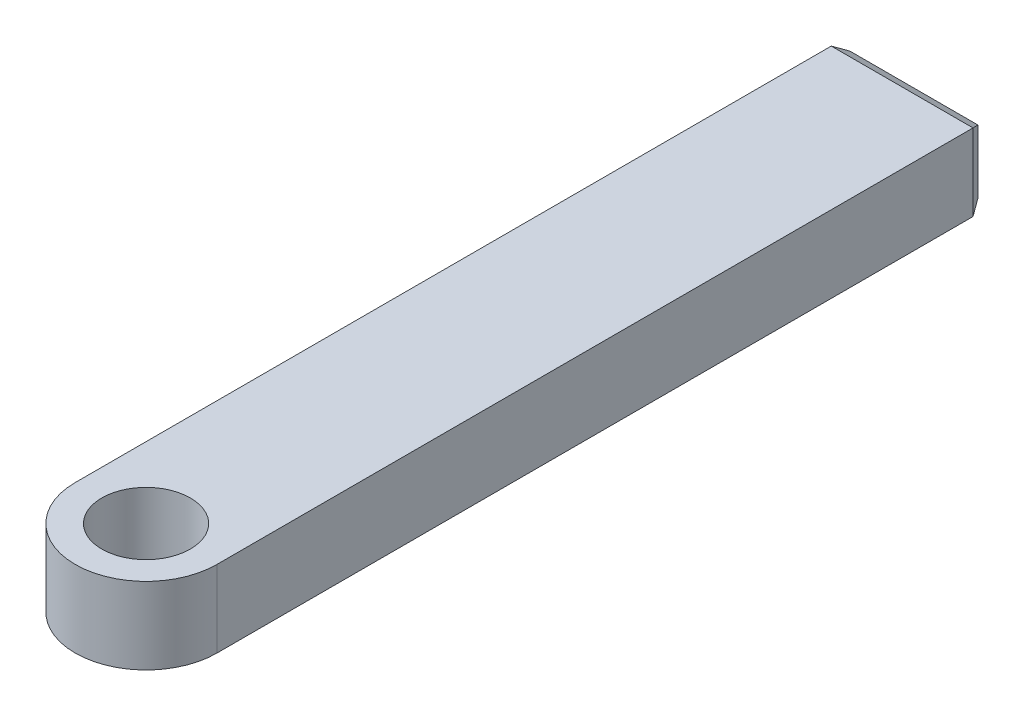
SolidWorks part; units mm, degrees
ref_plane "Спереди" through (0, 0, 0) normal (0, 0, 1) x (1, 0, 0)
ref_plane "Сверху" through (0, 0, 0) normal (0, 1, 0) x (1, 0, 0)
ref_plane "Справа" through (0, 0, 0) normal (1, 0, 0) x (0, 0, -1)
sketch "Sketch1" plane through (0, 0, 0) normal (0, 1, 0) x (1, 0, 0)
  line L0 (-6, 0) -> (-6, 65)
  line L1 (-6, 65) -> (6, 65)
  line L2 (6, 65) -> (6, 0)
  circle A0 centre (0, 0) radius 3.75
  circle A1 centre (0, 0) radius 6 construction
  arc A2 (-6, 0) -> (6, 0) centre (0, 0) ccw
  point P8 (-6, 0)
  dimension "D1" = 12
  dimension "D2" = 7.5
  dimension "D3" = 65
extrude "Boss-Extrude1" add sketch "Sketch1" along normal blind 6.5
chamfer "Chamfer1" distance 1 angle 30 4 edges at (6, 3.25, -65) (0, 6.5, -65) (-6, 3.25, -65) (0, 0, -65)
